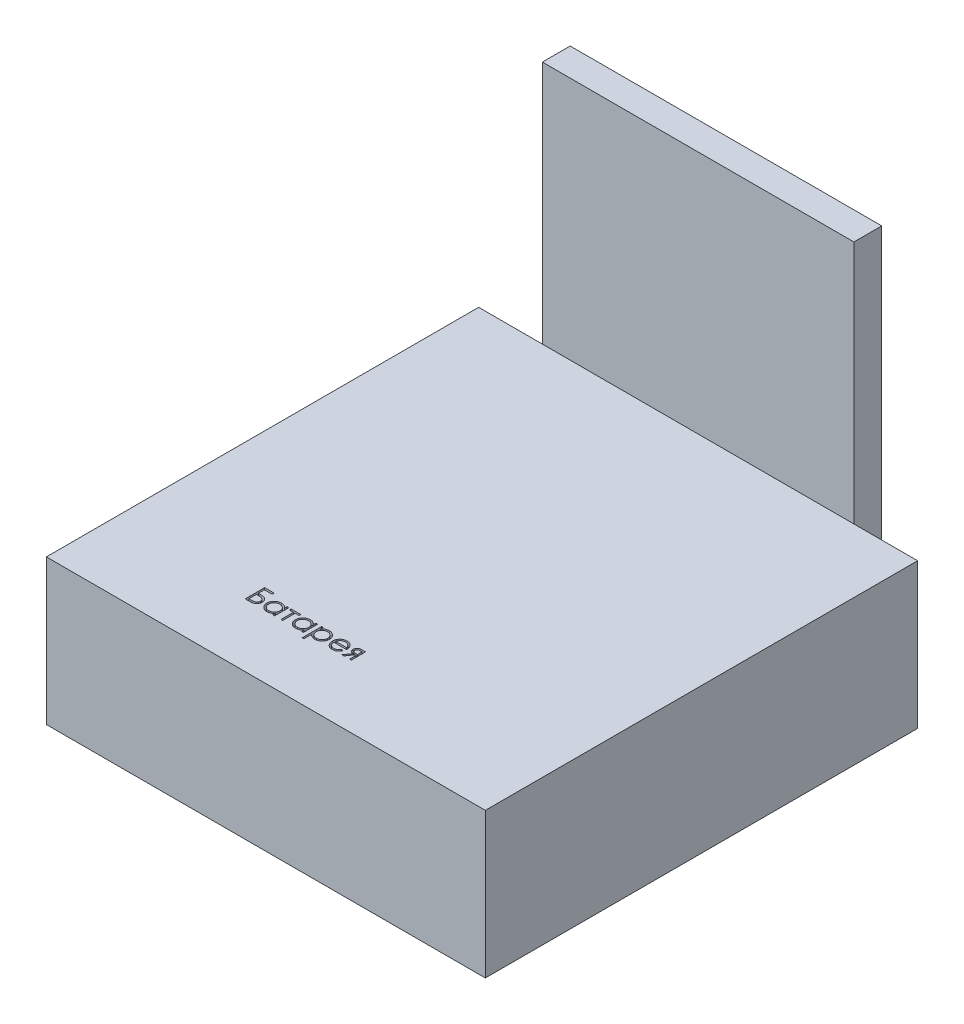
SolidWorks part; units mm, degrees
material "Пластичное железо"
ref_plane "Спереди" through (0, 0, 0) normal (0, 0, 1) x (1, 0, 0)
ref_plane "Сверху" through (0, 0, 0) normal (0, 1, 0) x (1, 0, 0)
ref_plane "Справа" through (0, 0, 0) normal (1, 0, 0) x (0, 0, -1)
sketch "Эскиз1" plane through (0, 0, 0) normal (0, 1, 0) x (1, 0, 0)
  line L1 (-39.45, 38.85) -> (39.45, 38.85)
  line L2 (-39.45, 38.85) -> (-39.45, -38.85)
  line L3 (-39.45, -38.85) -> (39.45, -38.85)
  line L4 (39.45, 38.85) -> (39.45, -38.85)
  line L5 (-39.45, 38.85) -> (39.45, -38.85) construction
  line L6 (-39.45, -38.85) -> (39.45, 38.85) construction
  point P0 (0, 0)
  dimension "D1" = 78.9
  dimension "D2" = 77.7
extrude "Бобышка-Вытянуть1" add sketch "Эскиз1" along normal blind 26.1
sketch "Эскиз2" plane through (0, 0, -38.85) normal (0, 0, -1) x (-1, 0, 0)
  line L0 (0, 0) -> (-28, 0) construction
  line L1 (-39.45, 0) -> (39.45, 0) construction
  line L3 (-28, 0) -> (28, 0)
  line L4 (-28, 0) -> (-28, 70)
  line L5 (-28, 70) -> (28, 70)
  line L6 (28, 0) -> (28, 70)
extrude "Бобышка-Вытянуть2" add sketch "Эскиз2" along normal blind 5
sketch "Эскиз3" plane through (0, 26.1, 0) normal (0, 1, 0) x (1, 0, 0)
  text T0 "Батарея"
extrude "Вырез-Вытянуть1" cut sketch "Эскиз3" against normal blind 2
